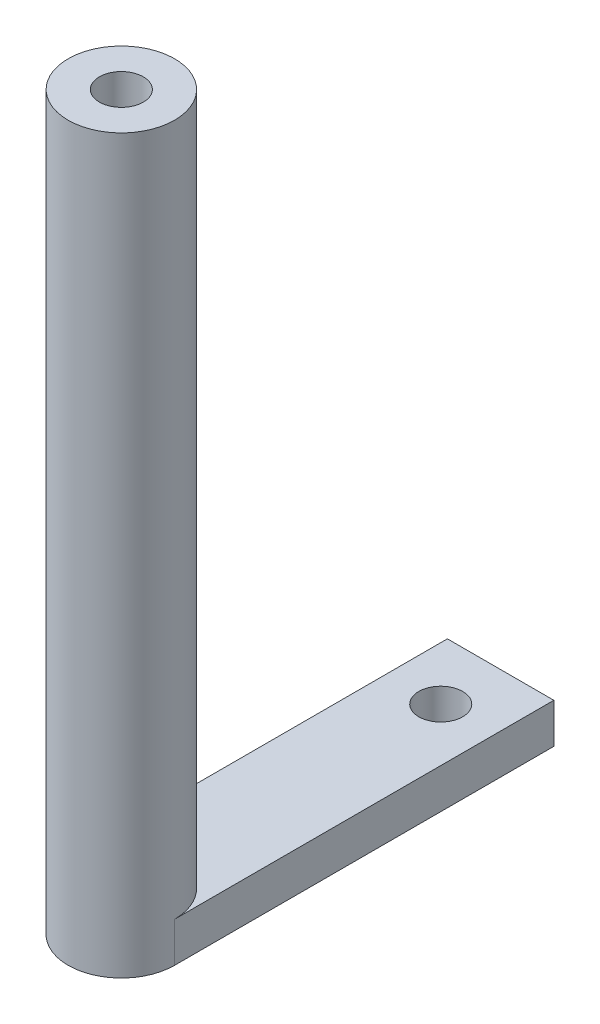
SolidWorks part; units mm, degrees
ref_plane "Ebene vorne" through (0, 0, 0) normal (0, 0, 1) x (1, 0, 0)
ref_plane "Ebene oben" through (0, 0, 0) normal (0, 1, 0) x (1, 0, 0)
ref_plane "Ebene rechts" through (0, 0, 0) normal (1, 0, 0) x (0, 0, -1)
sketch "Skizze2" plane through (0, 0, 0) normal (0, 1, 0) x (1, 0, 0)
  line L1 (-4, -4.5) -> (4, -4.5)
  line L2 (-4, -4.5) -> (-4, 28.5)
  line L3 (-4, 28.5) -> (4, 28.5)
  line L4 (4, -4.5) -> (4, 28.5)
  line L5 (-4, -4.5) -> (4, 28.5) construction
  line L6 (-4, 28.5) -> (4, -4.5) construction
  circle A0 centre (0, 24) radius 1.65
  circle A1 centre (0, 0) radius 4
  point P4 (0, 12)
  dimension "D5" = 3.3
  dimension "D1" = 8
  dimension "D2" = 33
  dimension "D3" = 4.5
  dimension "D4" = 4
  dimension "D6" = 4
  dimension "D7" = 4.5
extrude "Aufsatz-Linear austragen1" add sketch "Skizze2" along normal blind 3 contours A1 L4 L3 L2 A0 | A1
sketch "Skizze3" plane through (0, 3, 0) normal (0, 1, 0) x (1, 0, 0)
  circle A0 centre (0, 0) radius 4
  dimension "D1" = 8
extrude "Aufsatz-Linear austragen2" add sketch "Skizze3" along normal blind 52
sketch "Skizze4" plane through (0, 55, 0) normal (0, 1, 0) x (1, 0, 0)
  circle A0 centre (0, 0) radius 1.65
  dimension "D1" = 3.3
extrude "Schnitt-Linear austragen1" cut sketch "Skizze4" against normal blind 10
